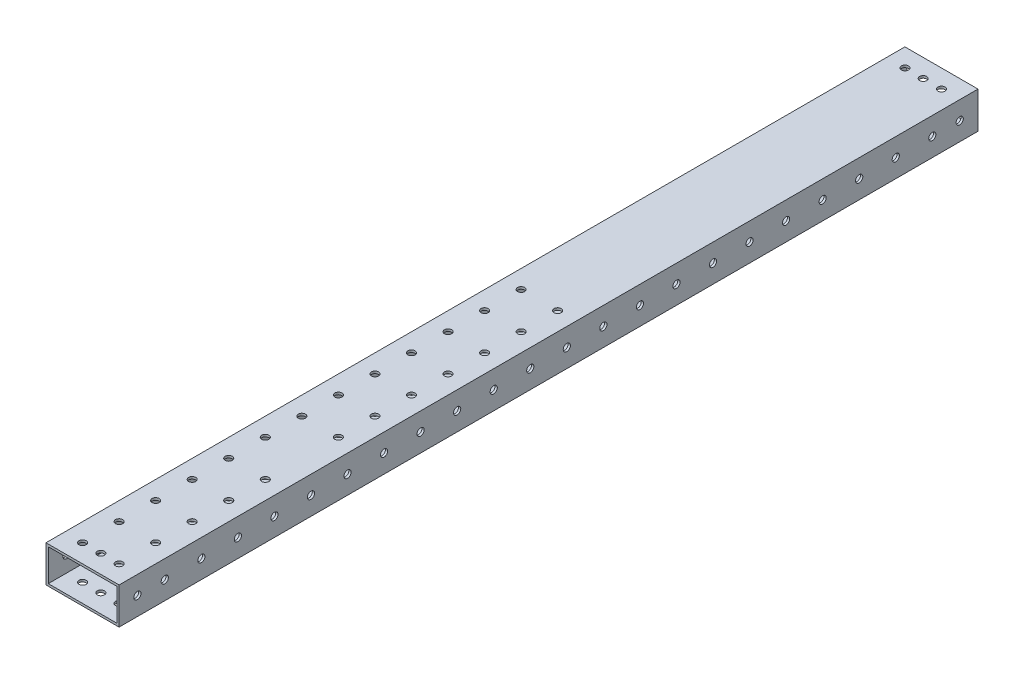
SolidWorks part; units mm, degrees
material "6061-T6 (SS)"
ref_plane "Front Plane" through (0, 0, 0) normal (0, 0, 1) x (1, 0, 0)
ref_plane "Top Plane" through (0, 0, 0) normal (0, 1, 0) x (1, 0, 0)
ref_plane "Right Plane" through (0, 0, 0) normal (1, 0, 0) x (0, 0, -1)
sketch "Sketch1" plane through (0, 0, 0) normal (0, 0, 1) x (1, 0, 0)
  line L1 (0, 0) -> (50.8, 0)
  line L2 (0, 0) -> (0, 25.4)
  line L3 (0, 25.4) -> (50.8, 25.4)
  line L4 (50.8, 0) -> (50.8, 25.4)
  dimension "D1" = 50.8
  dimension "D2" = 25.4
extrude "Boss-Extrude1" add sketch "Sketch1" along normal mid plane 596.9
shell "Shell1" thickness 1.5875
sketch "Sketch2" plane through (0, 25.4, 0) normal (0, 1, 0) x (1, 0, 0)
  line L0 (50.8, -298.45) -> (50.8, 298.45) construction
  line L1 (50.8, -298.45) -> (0, -298.45) construction
  circle A0 centre (38.1, -285.75) radius 2.4892
  circle A1 centre (25.4, -285.75) radius 2.4892
  circle A2 centre (12.7, -285.75) radius 2.4892
  dimension "D1" = 4.9784
  dimension "D2" = 12.7
  dimension "D3" = 12.7
  dimension "D4" = 12.7
  dimension "D5" = 12.7
extrude "Cut-Extrude1" cut sketch "Sketch2" against normal through all
sketch "Sketch3" plane through (50.8, 0, 0) normal (1, 0, 0) x (0, 0, -1)
  line L0 (-298.45, 25.4) -> (298.45, 25.4) construction
  line L1 (-298.45, 0) -> (-298.45, 25.4) construction
  circle A0 centre (-285.75, 12.7) radius 2.4892
  dimension "D1" = 4.9784
  dimension "D2" = 12.7
  dimension "D3" = 12.7
extrude "Cut-Extrude2" cut sketch "Sketch3" against normal through all
mirror "Mirror1" about plane through (0, 0, 0) normal (0, 0, 1) of "Cut-Extrude1", "Cut-Extrude2"
sketch "Sketch4" plane through (50.8, 0, 0) normal (1, 0, 0) x (0, 0, -1)
  line L0 (-285.75, 12.7) -> (-266.7, 12.7) construction
  line L1 (-298.45, 0) -> (298.45, 0) construction
  line L2 (-298.45, 0) -> (-298.45, 25.4) construction
  circle A0 centre (-266.7, 12.7) radius 2.4892
  dimension "D1" = 4.9784
  dimension "D2" = 31.75
extrude "Cut-Extrude3" cut sketch "Sketch4" against normal through all and the other way through all
pattern_linear "LPattern1" count 22 spacing 25.4 along (0, 0, -1) of "Cut-Extrude3"
sketch "Sketch5" plane through (0, 0, 0) normal (0, -1, 0) x (1, 0, 0)
  circle A0 centre (12.7, 158.75) radius 2.4892 construction
  circle A1 centre (12.7, 184.15) radius 2.4892 construction
  circle A2 centre (38.1, 184.15) radius 2.4892 construction
  circle A3 centre (38.1, 209.55) radius 2.4892 construction
  circle A4 centre (12.7, 209.55) radius 2.4892 construction
  circle A5 centre (12.7, 234.95) radius 2.4892 construction
  circle A6 centre (38.1, 234.95) radius 2.4892 construction
  circle A7 centre (38.1, 260.35) radius 2.4892 construction
  circle A8 centre (12.7, 260.35) radius 2.4892 construction
  circle A9 centre (12.7, 158.75) radius 2.4892
  circle A10 centre (12.7, 184.15) radius 2.4892
  circle A11 centre (38.1, 184.15) radius 2.4892
  circle A12 centre (38.1, 209.55) radius 2.4892
  circle A13 centre (12.7, 209.55) radius 2.4892
  circle A14 centre (12.7, 234.95) radius 2.4892
  circle A15 centre (38.1, 234.95) radius 2.4892
  circle A16 centre (38.1, 260.35) radius 2.4892
  circle A17 centre (12.7, 260.35) radius 2.4892
  circle A18 centre (12.7, 31.75) radius 2.4892 construction
  circle A19 centre (38.1, 31.75) radius 2.4892 construction
  circle A20 centre (12.7, 57.15) radius 2.4892 construction
  circle A21 centre (38.1, 57.15) radius 2.4892 construction
  circle A22 centre (12.7, 82.55) radius 2.4892 construction
  circle A23 centre (38.1, 82.55) radius 2.4892 construction
  circle A24 centre (38.1, 107.95) radius 2.4892 construction
  circle A25 centre (38.1, 133.35) radius 2.4892 construction
  circle A26 centre (12.7, 107.95) radius 2.4892 construction
  circle A27 centre (12.7, 133.35) radius 2.4892 construction
  circle A28 centre (12.7, 31.75) radius 2.4892
  circle A29 centre (38.1, 31.75) radius 2.4892
  circle A30 centre (12.7, 57.15) radius 2.4892
  circle A31 centre (38.1, 57.15) radius 2.4892
  circle A32 centre (12.7, 82.55) radius 2.4892
  circle A33 centre (38.1, 82.55) radius 2.4892
  circle A34 centre (38.1, 107.95) radius 2.4892
  circle A35 centre (38.1, 133.35) radius 2.4892
  circle A36 centre (12.7, 107.95) radius 2.4892
  circle A37 centre (12.7, 133.35) radius 2.4892
  circle A38 centre (38.1, 6.35) radius 2.4892 construction
  circle A39 centre (38.1, -19.05) radius 2.4892 construction
  circle A40 centre (12.7, -19.05) radius 2.4892 construction
  circle A41 centre (12.7, 6.35) radius 2.4892 construction
  circle A42 centre (38.1, 6.35) radius 2.4892
  circle A43 centre (38.1, -19.05) radius 2.4892
  circle A44 centre (12.7, -19.05) radius 2.4892
  circle A45 centre (12.7, 6.35) radius 2.4892
extrude "Cut-Extrude4" cut sketch "Sketch5" against normal through all
